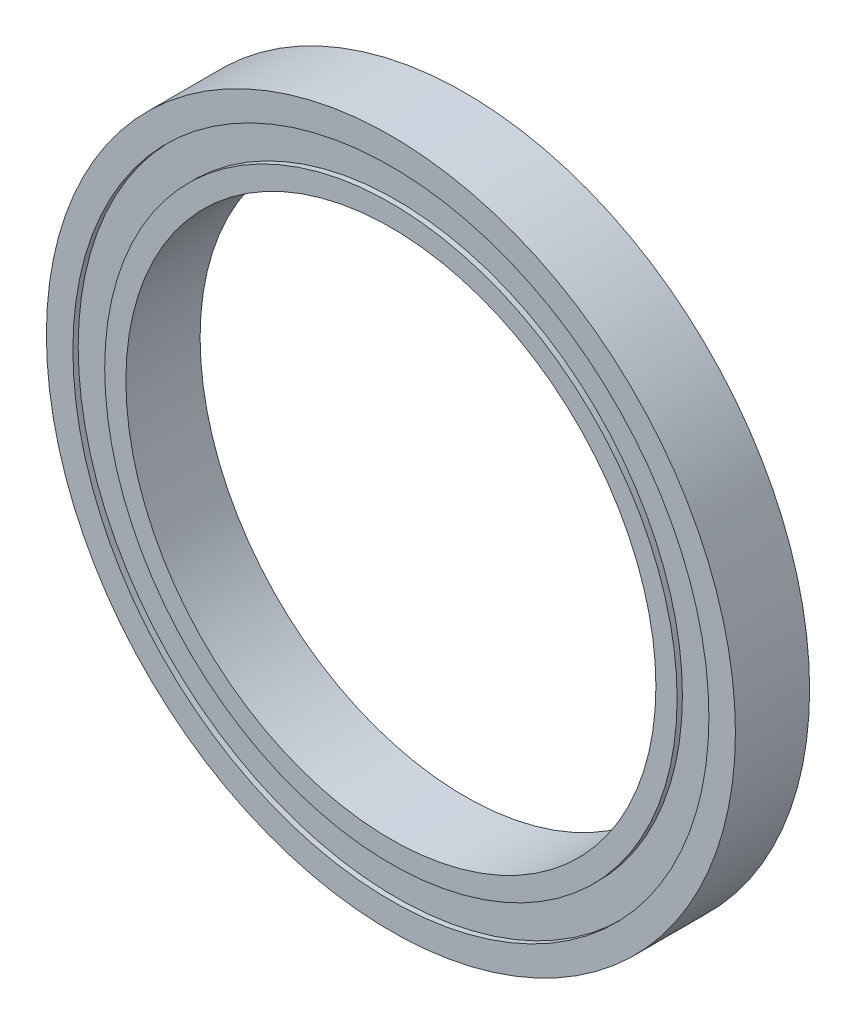
SolidWorks part; units mm, degrees
ref_plane "前视基准面" through (0, 0, 0) normal (0, 0, 1) x (1, 0, 0)
ref_plane "上视基准面" through (0, 0, 0) normal (0, 1, 0) x (1, 0, 0)
ref_plane "右视基准面" through (0, 0, 0) normal (1, 0, 0) x (0, 0, -1)
other "Configuration Table"
sketch "草图1" plane through (0, 0, 0) normal (0, 0, 1) x (1, 0, 0)
  circle A0 centre (0, 0) radius 25
  circle A1 centre (0, 0) radius 32.5
  dimension "D1" = 50
  dimension "D2" = 65
extrude "凸台-拉伸1" add sketch "草图1" along normal mid plane 7
sketch "草图2" plane through (0, 0, 3.5) normal (0, 0, 1) x (1, 0, 0)
  circle A0 centre (0, 0) radius 27
  circle A1 centre (0, 0) radius 30
  dimension "D1" = 54
  dimension "D2" = 60
extrude "切除-拉伸1" cut sketch "草图2" against normal blind 0.5
mirror "镜向1" about plane through (0, 0, 0) normal (0, 0, 1) of "切除-拉伸1"
